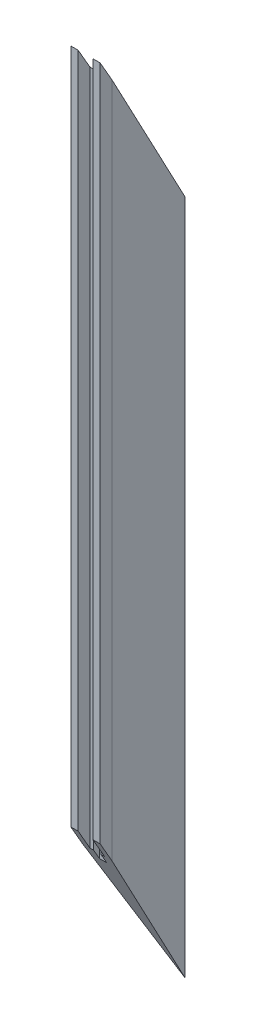
SolidWorks part; units mm, degrees
material "AISI 316 Stainless Steel Sheet (SS)"
ref_plane "Front Plane" through (0, 0, 0) normal (0, 0, 1) x (1, 0, 0)
ref_plane "Top Plane" through (0, 0, 0) normal (0, 1, 0) x (1, 0, 0)
ref_plane "Right Plane" through (0, 0, 0) normal (1, 0, 0) x (0, 0, -1)
sketch "Sketch1" plane through (0, 0, 0) normal (0, 1, 0) x (1, 0, 0)
  line L0 (0, 0) -> (0, 38.1) construction
  line L1 (0, 38.1) -> (-6.35, 0)
  line L2 (0, 38.1) -> (6.35, 0)
  line L3 (0, 18.7872) -> (3.2182, -0.522) construction
  line L4 (0, 18.7872) -> (-3.2182, -0.522) construction
  line L5 (0, 0) -> (3.175, 0) construction
  line L6 (0, 0) -> (-3.175, 0) construction
  line L7 (-3.175, 0) -> (-3.175, -5.08)
  line L8 (-3.175, -5.08) -> (-6.35, -5.08)
  line L9 (-6.35, -5.08) -> (-6.35, 0)
  line L10 (3.175, 0) -> (3.175, -5.08)
  line L11 (3.175, -5.08) -> (6.35, -5.08)
  line L12 (6.35, -5.08) -> (6.35, 0)
  line L13 (-3.175, 0) -> (-1.5875, 0)
  line L14 (-1.5875, 0) -> (-1.5875, 9.2622) construction
  line L15 (-1.5875, 9.2622) -> (1.5875, 9.2622) construction
  line L16 (1.5875, 9.2622) -> (1.5875, 0) construction
  line L17 (1.5875, 0) -> (3.175, 0)
  line L19 (-1.5875, 0) -> (-1.5875, 2.54)
  line L20 (-1.5875, 2.54) -> (1.5875, 2.54)
  line L21 (1.5875, 2.54) -> (1.5875, 0)
  dimension "D7" = 1.5875
  dimension "D1" = 38.1
  dimension "D2" = 6.35
  dimension "D3" = 6.35
  dimension "D5" = 3.175
  dimension "D6" = 3.175
  dimension "D8" = 5.08
  dimension "D9" = 5.08
  dimension "D10" = 2.54
  dimension "D4" = 3.175
extrude "Boss-Extrude1" add sketch "Sketch1" along normal blind 369.316
sketch "Sketch2" plane through (-6.35, 0, 0) normal (-1, 0, 0) x (0, 0, 1)
  line L0 (5.08, 369.316) -> (-38.1, 294.2237)
  line L1 (-38.1, 369.316) -> (-38.1, 0) construction
  line L2 (5.08, 369.316) -> (5.08, 0) construction
  line L3 (-38.1, 294.2237) -> (-38.1, 369.316)
  line L4 (-38.1, 369.316) -> (5.08, 369.316)
  dimension "D1" = 29.9
extrude "Cut-Extrude1" cut sketch "Sketch2" against normal blind 17.526
sketch "Sketch3" plane through (-6.35, 0, 0) normal (-1, 0, 0) x (0, 0, 1)
  line L0 (5.08, 76.2) -> (-38.1, 1.1077)
  line L1 (5.08, 369.316) -> (5.08, 0) construction
  line L2 (-38.1, 1.1077) -> (-38.1, 0)
  line L3 (-38.1, 0) -> (5.08, 0)
  line L4 (5.08, 0) -> (5.08, 76.2)
  dimension "D1" = 150.1
  dimension "D2" = 293.116
extrude "Cut-Extrude2" cut sketch "Sketch3" against normal blind 17.526
